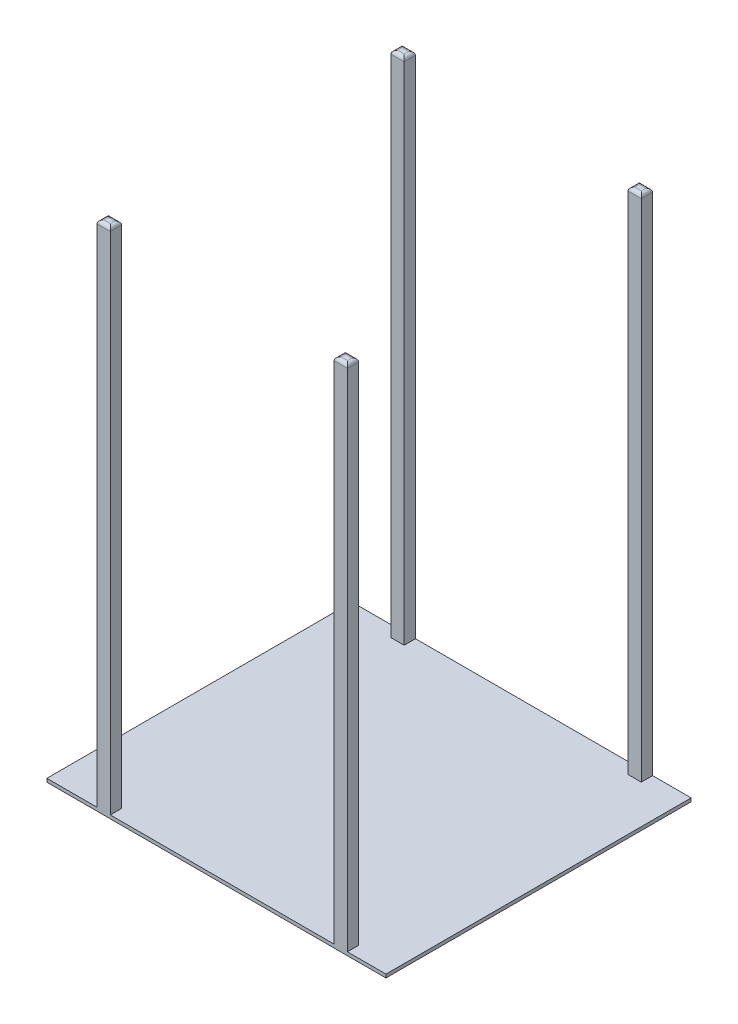
SolidWorks part; units mm, degrees
ref_plane "Front Plane" through (0, 0, 0) normal (0, 0, 1) x (1, 0, 0)
ref_plane "Top Plane" through (0, 0, 0) normal (0, 1, 0) x (1, 0, 0)
ref_plane "Right Plane" through (0, 0, 0) normal (1, 0, 0) x (0, 0, -1)
sketch "Sketch1" plane through (0, 0, 0) normal (0, 1, 0) x (1, 0, 0)
  line L1 (-500, -450) -> (500, -450)
  line L2 (-500, -450) -> (-500, 450)
  line L3 (-500, 450) -> (500, 450)
  line L4 (500, -450) -> (500, 450)
  line L5 (-500, -450) -> (500, 450) construction
  line L6 (-500, 450) -> (500, -450) construction
  point P0 (0, 0)
  dimension "D1" = 1000
  dimension "D2" = 900
extrude "Boss-Extrude1" add sketch "Sketch1" along normal mid plane 10
sketch "Sketch2" plane through (0, 5, 0) normal (0, 1, 0) x (1, 0, 0)
  line L0 (-500, -450) -> (500, -450) construction
  line L1 (-352.1503, -450) -> (-312.9333, -450)
  line L2 (-352.1503, -450) -> (-352.1503, -416.631)
  line L3 (-352.1503, -416.631) -> (-312.9333, -416.631)
  line L4 (-312.9333, -450) -> (-312.9333, -416.631)
  line L5 (-500, 0) -> (500, 0) construction
  line L6 (347.0667, -450) -> (386.2837, -450)
  line L7 (347.0667, -450) -> (347.0667, -416.631)
  line L8 (347.0667, -416.631) -> (386.2837, -416.631)
  line L9 (386.2837, -450) -> (386.2837, -416.631)
  line L10 (-500, 450) -> (-500, -450) construction
  line L11 (500, -450) -> (500, 450) construction
  line L12 (386.2837, 450) -> (386.2837, 416.631)
  line L13 (347.0667, 416.631) -> (386.2837, 416.631)
  line L14 (347.0667, 450) -> (347.0667, 416.631)
  line L15 (347.0667, 450) -> (386.2837, 450)
  line L16 (-312.9333, 450) -> (-312.9333, 416.631)
  line L17 (-352.1503, 416.631) -> (-312.9333, 416.631)
  line L18 (-352.1503, 450) -> (-352.1503, 416.631)
  line L19 (-352.1503, 450) -> (-312.9333, 450)
  dimension "D1" = 660
extrude "Boss-Extrude2" add sketch "Sketch2" along normal blind 1500
fillet "Fillet1" radius 10 16 edges at (386.2837, 1505, -433.3155) (366.6752, 1505, -416.631) (347.0667, 1505, -433.3155) (366.6752, 1505, -450) (366.6752, 1505, 416.631) (386.2837, 1505, 433.3155) (366.6752, 1505, 450) (347.0667, 1505, 433.3155) (-332.5418, 1505, 416.631) (-312.9333, 1505, 433.3155) (-332.5418, 1505, 450) (-352.1503, 1505, 433.3155) (-312.9333, 1505, -433.3155) (-332.5418, 1505, -416.631) (-352.1503, 1505, -433.3155) (-332.5418, 1505, -450)
